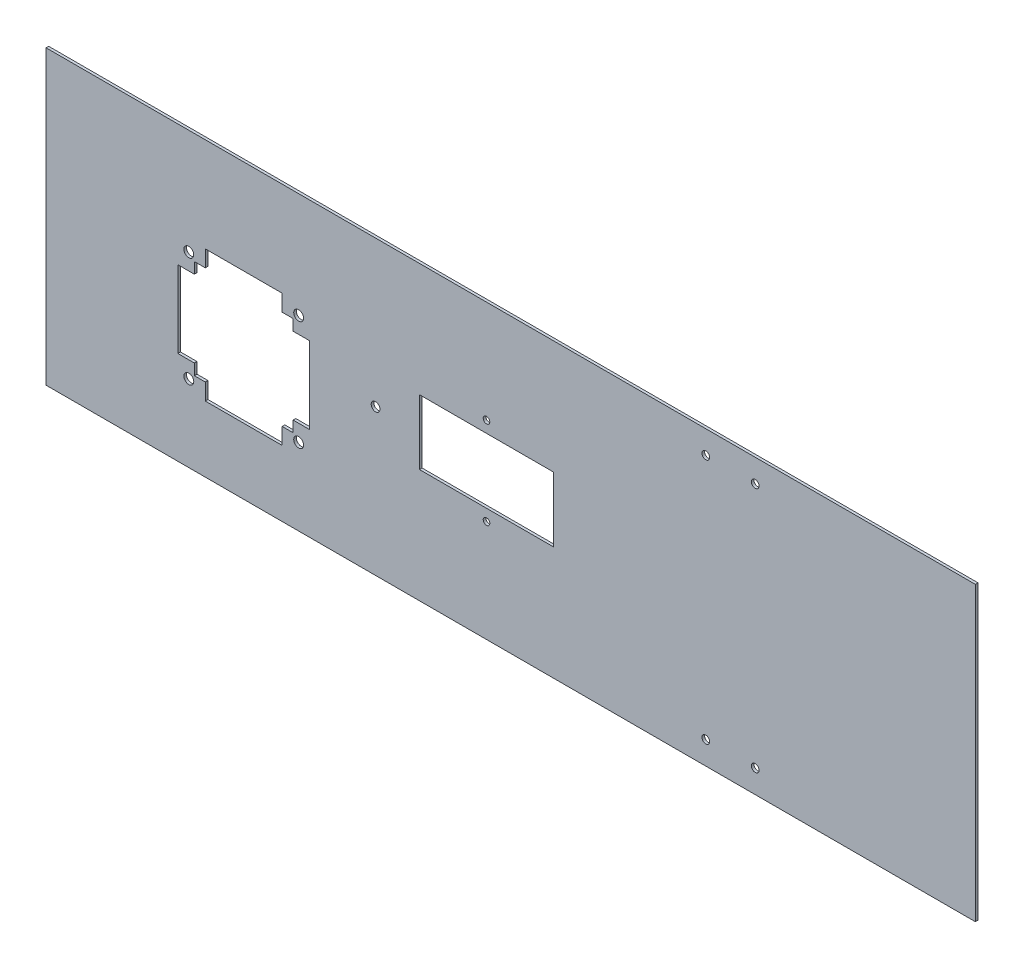
SolidWorks part; units mm, degrees
ref_plane "Plan de face" through (0, 0, 0) normal (0, 0, 1) x (1, 0, 0)
ref_plane "Plan de dessus" through (0, 0, 0) normal (0, 1, 0) x (1, 0, 0)
ref_plane "Plan de droite" through (0, 0, 0) normal (1, 0, 0) x (0, 0, -1)
sketch "Esquisse1" plane through (0, 0, 0) normal (0, 0, 1) x (1, 0, 0)
  line L0 (-482.2528, 72.1267) -> (-437.2528, 117.1267) construction
  line L1 (-126.7528, 34.6267) -> (-549.7528, 34.6267)
  line L2 (-126.7528, 34.6267) -> (-126.7528, 167.6267)
  line L3 (-126.7528, 167.6267) -> (-549.7528, 167.6267)
  line L4 (-549.7528, 34.6267) -> (-549.7528, 167.6267)
  line L5 (-482.2528, 117.1267) -> (-437.2528, 117.1267)
  line L6 (-482.2528, 117.1267) -> (-482.2528, 72.1267)
  line L7 (-482.2528, 72.1267) -> (-437.2528, 72.1267)
  line L8 (-437.2528, 117.1267) -> (-437.2528, 72.1267)
  line L9 (-477.2528, 117.1267) -> (-442.2528, 117.1267)
  line L10 (-477.2528, 117.1267) -> (-477.2528, 124.6267)
  line L11 (-477.2528, 124.6267) -> (-442.2528, 124.6267)
  line L12 (-442.2528, 117.1267) -> (-442.2528, 124.6267)
  line L13 (-437.2528, 112.1267) -> (-429.7528, 112.1267)
  line L14 (-437.2528, 112.1267) -> (-437.2528, 77.1267)
  line L15 (-437.2528, 77.1267) -> (-429.7528, 77.1267)
  line L16 (-429.7528, 112.1267) -> (-429.7528, 77.1267)
  line L17 (-442.2528, 72.1267) -> (-477.2528, 72.1267)
  line L18 (-442.2528, 72.1267) -> (-442.2528, 64.6267)
  line L19 (-442.2528, 64.6267) -> (-477.2528, 64.6267)
  line L20 (-477.2528, 72.1267) -> (-477.2528, 64.6267)
  line L21 (-482.2528, 112.1267) -> (-489.7528, 112.1267)
  line L22 (-482.2528, 112.1267) -> (-482.2528, 77.1267)
  line L23 (-482.2528, 77.1267) -> (-489.7528, 77.1267)
  line L24 (-489.7528, 112.1267) -> (-489.7528, 77.1267)
  line L25 (-482.2528, 117.1267) -> (-437.2528, 72.1267) construction
  line L26 (-434.7528, 69.6267) -> (-484.7528, 119.6267) construction
  line L27 (-484.7528, 69.6267) -> (-434.7528, 119.6267) construction
  line L28 (-274.7516, 160.1267) -> (-274.7516, 42.1267) construction
  line L29 (-379.7528, 115.8767) -> (-318.7528, 115.8767)
  line L30 (-379.7528, 115.8767) -> (-379.7528, 86.3767)
  line L31 (-379.7528, 86.3767) -> (-318.7528, 86.3767)
  line L32 (-318.7528, 115.8767) -> (-318.7528, 86.3767)
  line L33 (-274.7516, 42.1267) -> (-201.2516, 42.1267) construction
  line L34 (-201.2516, 42.1267) -> (-201.2516, 160.1267) construction
  line L35 (-201.2516, 160.1267) -> (-274.7516, 160.1267) construction
  circle A0 centre (-434.7528, 69.6267) radius 2.25
  circle A1 centre (-484.7528, 69.6267) radius 2.25
  circle A2 centre (-484.7528, 119.6267) radius 2.25
  circle A3 centre (-434.7528, 119.6267) radius 2.25
  circle A4 centre (-349.2528, 81.1267) radius 1.5
  circle A5 centre (-349.2528, 121.1267) radius 1.5
  circle A6 centre (-399.7528, 101.1267) radius 2
  circle A7 centre (-249.4516, 157.1267) radius 1.75
  circle A8 centre (-226.9516, 157.1267) radius 1.75
  circle A9 centre (-226.9516, 45.1267) radius 1.75
  circle A10 centre (-249.4516, 45.1267) radius 1.75
  dimension "D17" = 5
  dimension "D18" = 5
  dimension "D19" = 2
  dimension "D20" = 2
  dimension "D21" = 4.5
  dimension "D23" = 29.5
  dimension "D24" = 61
  dimension "D25" = 3
  dimension "D26" = 3
  dimension "D27" = 40
  dimension "D28" = 30.5
  dimension "D29" = 30.5
  dimension "D30" = 5.25
  dimension "D33" = 4
  dimension "D34" = 20
  dimension "D35" = 3.5
  dimension "D40" = 25.3
  dimension "D41" = 3
  dimension "D44" = 14.75
  dimension "D1" = 133
  dimension "D2" = 423
  dimension "D3" = 60
  dimension "D4" = 60
  dimension "D5" = 45
  dimension "D6" = 45
  dimension "D7" = 7.5
  dimension "D8" = 5
  dimension "D9" = 5
  dimension "D10" = 5
  dimension "D11" = 5
  dimension "D12" = 7.5
  dimension "D13" = 5
  dimension "D14" = 5
  dimension "D15" = 5
  dimension "D16" = 5
  dimension "D22" = 60
  dimension "D31" = 51.75
  dimension "D32" = 50
  dimension "D38" = 118
  dimension "D39" = 73.5
  dimension "D42" = 15
  dimension "D43" = 30
  dimension "D36" = 2
  dimension "D37" = 2
extrude "Boss.-Extru.1" add sketch "Esquisse1" along normal blind 1.2 contours L4 L1 L2 L3 A6 A5 A4 A3 A2 A1 A0 L24 L21 L6 L5 L10 L11 L12 L8 L13 L16 L15 L7 L18 L19 L20 L23 L29 L32 L31 L30
